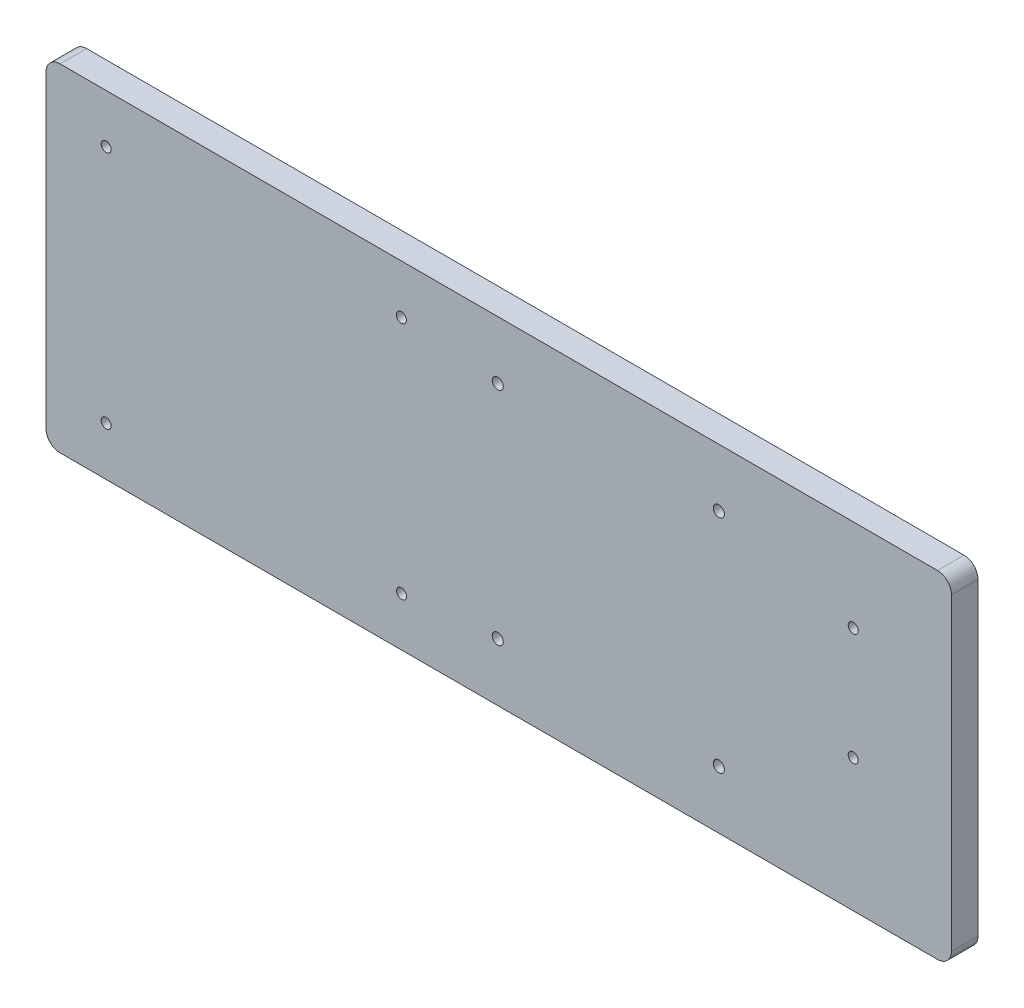
SolidWorks part; units mm, degrees
ref_plane "Front Plane" through (0, 0, 0) normal (0, 0, 1) x (1, 0, 0)
ref_plane "Top Plane" through (0, 0, 0) normal (0, 1, 0) x (1, 0, 0)
ref_plane "Right Plane" through (0, 0, 0) normal (1, 0, 0) x (0, 0, -1)
other "Configuration Table"
sketch "Sketch1" plane through (0, 0, 0) normal (0, 0, 1) x (1, 0, 0)
  line L0 (195.2804, 17.3) -> (195.2804, 68.1) construction
  line L1 (3.175, 0) -> (201.6304, 0)
  line L2 (0, 3.175) -> (0, 73.025)
  line L3 (3.175, 76.2) -> (201.6304, 76.2)
  line L4 (204.8054, 3.175) -> (204.8054, 73.025)
  arc A0 (3.175, 0) -> (0, 3.175) centre (3.175, 3.175) cw
  arc A1 (201.6304, 0) -> (204.8054, 3.175) centre (201.6304, 3.175) ccw
  arc A2 (201.6304, 76.2) -> (204.8054, 73.025) centre (201.6304, 73.025) cw
  arc A3 (0, 73.025) -> (3.175, 76.2) centre (3.175, 73.025) cw
  point P9 (0, 0)
  point P16 (0, 76.2)
  dimension "D3" = 3.175
  dimension "D1" = 76.2
  dimension "D2" = 9.525
extrude "Boss-Extrude1" add sketch "Sketch1" along normal blind 6
hole_wizard "#4-40 Tapped Hole1" positions "Sketch2" profile "Sketch3" tap size "#4-40" standard "ANSI Inch" end condition through all
sketch "Sketch2" plane through (0, 0, 6) normal (0, 0, 1) x (1, 0, 0)
  point P0 (13.6017, 65.1891)
  point P3 (13.6017, 11.0363)
  point P6 (80.4291, 11.0617)
  point P9 (80.3783, 65.1383)
  point P12 (182.5804, 30)
  point P15 (182.5804, 55.4)
sketch "Sketch3" plane through (13.6017, 65.1891, 6) normal (1, 0, 0) x (0, -1, 0)
  line L0 (0, 0) -> (0, 6)
  line L1 (0, 6) -> (1.1303, 6)
  line L2 (1.1303, 6) -> (1.1303, 0)
  line L5 (1.1303, 0) -> (0, 0)
  line L11 (0, -6.35) -> (0, 107.95) construction
  dimension "Thru Tap Drill Dia." = 2.2606
  dimension "Thru Tap Drill Depth" = 6
cosmetic thread "Hole Thread1" parameters "D2"=2.8448
cosmetic thread "Hole Thread2" parameters "D2"=2.8448
cosmetic thread "Hole Thread3" parameters "D2"=2.8448
cosmetic thread "Hole Thread4" parameters "D2"=2.8448
cosmetic thread "Hole Thread5" parameters "D2"=2.8448
cosmetic thread "Hole Thread6" parameters "D2"=2.8448
hole_wizard "M3x0.5 Tapped Hole1" positions "Sketch4" profile "Sketch5" tap size "M3x0.5" standard "ANSI Metric" end condition through all
sketch "Sketch4" plane through (0, 0, 6) normal (0, 0, 1) x (1, 0, 0)
  point P0 (102.1804, 63.1)
  point P3 (152.1804, 63.1)
  point P6 (152.1804, 13.1)
  point P9 (102.1804, 13.1)
sketch "Sketch5" plane through (102.1804, 63.1, 6) normal (1, 0, 0) x (0, -1, 0)
  line L0 (0, 0) -> (0, 6)
  line L1 (0, 6) -> (1.25, 6)
  line L2 (1.25, 6) -> (1.25, 0)
  line L5 (1.25, 0) -> (0, 0)
  line L11 (0, -6.35) -> (0, 107.95) construction
  dimension "Thru Tap Drill Dia." = 2.5
  dimension "Thru Tap Drill Depth" = 6
cosmetic thread "Hole Thread7" parameters "D2"=3
cosmetic thread "Hole Thread8" parameters "D2"=3
cosmetic thread "Hole Thread9" parameters "D2"=3
cosmetic thread "Hole Thread10" parameters "D2"=3
